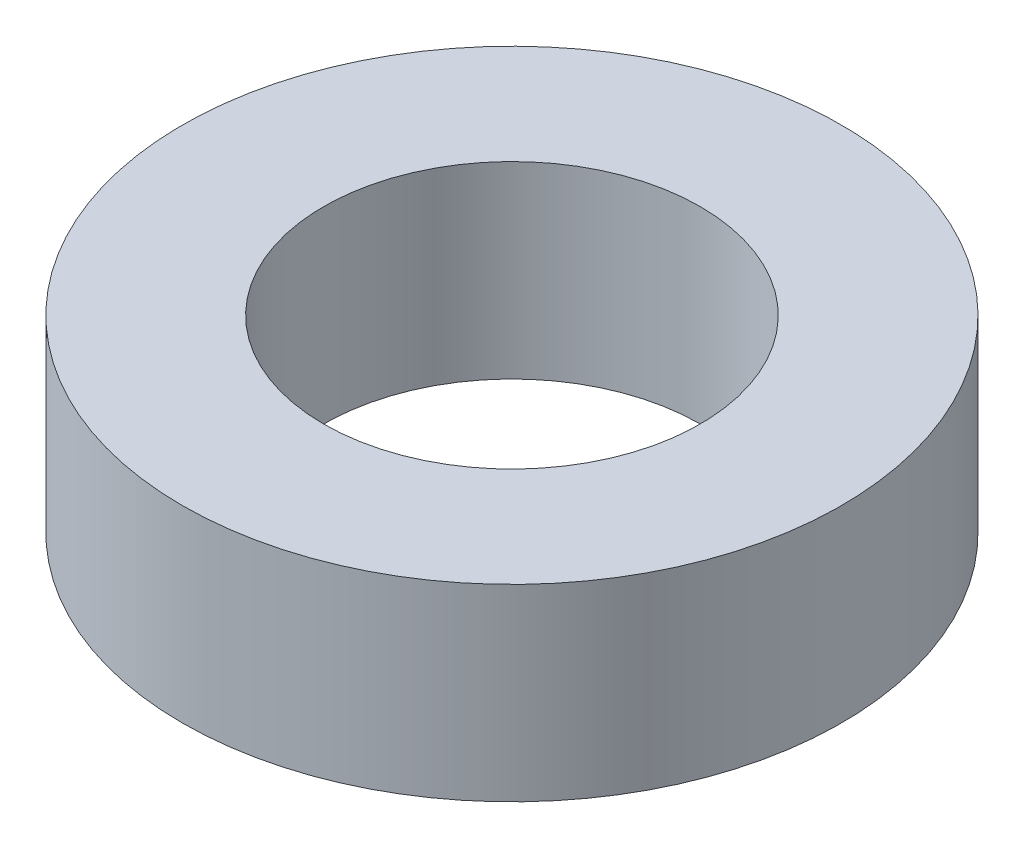
SolidWorks part; units mm, degrees
material "Cast Stainless Steel"
ref_plane "前视基准面" through (0, 0, 0) normal (0, 0, 1) x (1, 0, 0)
ref_plane "上视基准面" through (0, 0, 0) normal (0, 1, 0) x (1, 0, 0)
ref_plane "右视基准面" through (0, 0, 0) normal (1, 0, 0) x (0, 0, -1)
sketch "Sketch1" plane through (0, 0, 0) normal (0, 1, 0) x (1, 0, 0)
  circle A0 centre (0, 0) radius 17.5
  circle A1 centre (0, 0) radius 10
other "Pen Sketch1" parameters "D1"=97.8684, "D2"=11.5539
extrude "Boss-Extrude1" add sketch "Sketch1" along normal blind 10
